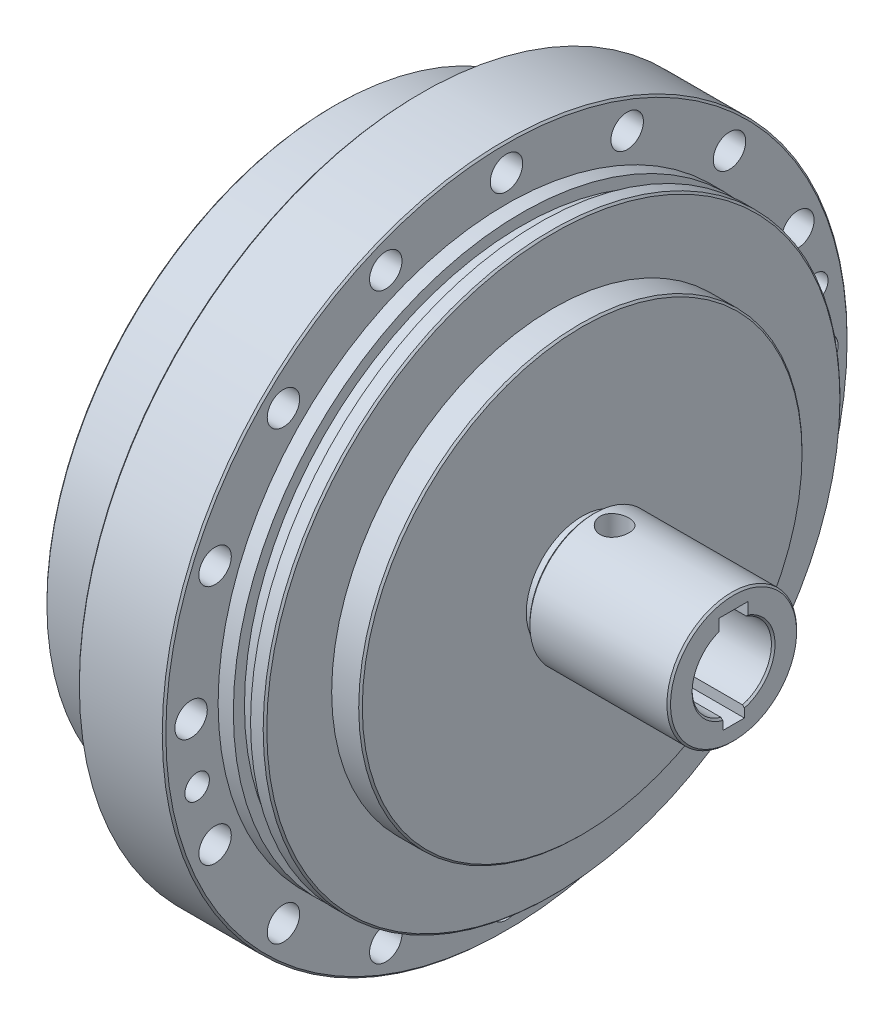
SolidWorks part; units mm, degrees
ref_plane "前视基准面" through (0, 0, 0) normal (0, 0, 1) x (1, 0, 0)
ref_plane "上视基准面" through (0, 0, 0) normal (0, 1, 0) x (1, 0, 0)
ref_plane "右视基准面" through (0, 0, 0) normal (1, 0, 0) x (0, 0, -1)
sketch "草图1" plane through (0, 0, 0) normal (0, 0, 1) x (1, 0, 0)
  line L0 (0, 0) -> (186.6546, 0) construction
  line L1 (3.8, 15.5) -> (3.8, 25)
  line L2 (3.8, 25) -> (0, 25)
  line L3 (0, 25) -> (0, 67.5)
  line L4 (0, 67.5) -> (7, 67.5)
  line L5 (7, 67.5) -> (7, 80)
  line L6 (7, 80) -> (31, 80)
  line L7 (31, 80) -> (31, 95)
  line L8 (31, 95) -> (55, 95)
  line L9 (55, 95) -> (55, 80)
  line L10 (55, 80) -> (59.22, 80)
  line L11 (59.22, 80) -> (59.22, 76.915)
  line L12 (59.22, 76.915) -> (64, 76.915)
  line L13 (64, 76.915) -> (64, 80)
  line L14 (64, 80) -> (68, 80)
  line L15 (68, 80) -> (68, 61.5)
  line L16 (76, 15.5) -> (3.8, 15.5)
  line L17 (56, 14.75) -> (56, 13.25)
  line L18 (68, 61.5) -> (76, 61.5)
  line L19 (76, 61.5) -> (76, 15.5)
  line L21 (3, 12) -> (3, 0)
  line L22 (79, 18) -> (118, 18)
  line L23 (118, 18) -> (118, 0)
  line L24 (79, 18) -> (79, 14.75)
  line L25 (79, 14.75) -> (56, 14.75)
  line L26 (3, 0) -> (118, 0)
  line L27 (56, 13.25) -> (33.25, 13.25)
  line L28 (33.25, 13.25) -> (32, 12)
  line L29 (32, 12) -> (3, 12)
  dimension "D1" = 3.8
  dimension "D3" = 67.5
  dimension "D4" = 7
  dimension "D5" = 31
  dimension "D6" = 80
  dimension "D7" = 95
  dimension "D8" = 24
  dimension "D9" = 80
  dimension "D10" = 68
  dimension "D11" = 4
  dimension "D12" = 4.78
  dimension "D13" = 76.915
  dimension "D14" = 61.5
  dimension "D15" = 76
  dimension "D16" = 31
  dimension "D17" = 53
  dimension "D18" = 29.5
  dimension "D19" = 24
  dimension "D20" = 3
  dimension "D21" = 25
  dimension "D22" = 18
  dimension "D23" = 115
  dimension "D24" = 76
  dimension "D25" = 26.5
  dimension "D26" = 135
  dimension "D27" = 29
revolve "旋转1" add sketch "草图1" angle 360 about L0
chamfer "倒角1" distance 0.5 angle 45 7 edges at (0, 0, 67.5) (68, 0, 80) (3.8, 0, 15.5) (55, 0, 95) (31, 0, 95) (7, 0, 80) (76, 0, 61.5)
sketch "草图2" plane through (55, 0, 0) normal (1, 0, 0) x (0, 0, -1)
  circle A0 centre (0, 87.5) radius 4.5
  circle A1 centre (0, 0) radius 87.5 construction
  dimension "D1" = 9
  dimension "D2" = 87.5
extrude "切除-拉伸1" cut sketch "草图2" against normal up to next
pattern_circular "阵列(圆周)1" count 16 over 360 about axis through (0, 0, 0) along (1, 0, 0) of "切除-拉伸1"
sketch "草图3" plane through (0, 0, 0) normal (-1, 0, 0) x (0, 0, 1)
  line L0 (0, 0) -> (28.1052, -40.1385) construction
  line L1 (0, 0) -> (0, -49) construction
  line L2 (0, 0) -> (-28.1052, -40.1385) construction
  line L3 (0, 0) -> (49, 0) construction
  line L4 (0, 0) -> (-28.1052, 40.1385) construction
  line L5 (0, 0) -> (28.1052, 40.1385) construction
  circle A0 centre (0, 0) radius 49 construction
  point P9 (0, 42.5)
  point P10 (0, -42.5)
  dimension "D1" = 98
  dimension "D2" = 35
  dimension "D3" = 85
sketch "草图5" plane through (31, 0, 0) normal (-1, 0, 0) x (0, 0, 1)
  line L0 (0, 0) -> (-85.8187, 17.0704) construction
  line L1 (0, 0) -> (-87.5, 0) construction
  line L2 (0, 0) -> (85.8187, -17.0704) construction
  dimension "D1" = 87.5
  dimension "D2" = 11.25
  dimension "D4" = 180
  dimension "D3" = 2
hole_wizard "M8 螺纹孔1" positions "3D草图2" profile "草图7" tap size "M8" standard "Gb" end condition through all
sketch3d "3D草图2"
  point P0 (31, 17.0704, -85.8187)
  point P3 (31, -17.0704, 85.8187)
sketch "草图7" plane through (31, 17.0704, -85.8187) normal (0, 1, 0) x (0, 0, 1)
  line L0 (0, 0) -> (0, 87)
  line L1 (0, 87) -> (3.4, 87)
  line L2 (3.4, 87) -> (3.4, 0)
  line L5 (3.4, 0) -> (0, 0)
  line L11 (0, -6.35) -> (0, 107.95) construction
  dimension "通孔螺纹孔钻头直径" = 6.8
  dimension "通孔螺纹孔钻头深度" = 87
cosmetic thread "孔螺蚊线7" parameters "D2"=8
cosmetic thread "孔螺蚊线8" parameters "D2"=8
hole_wizard "M14 螺纹孔1" positions "3D草图3" profile "草图8" tap size "M14" standard "Gb"
sketch3d "3D草图3"
  point P0 (0, -40.1385, -28.1052)
  point P6 (0, -40.1385, 28.1052)
  point P9 (0, 40.1385, 28.1052)
  point P15 (0, 40.1385, -28.1052)
  point P19 (0, -42.5, 0)
  point P22 (0, 42.5, 0)
sketch "草图8" plane through (0, -40.1385, -28.1052) normal (0, 1, 0) x (0, 0, 1)
  line L0 (0, 0) -> (0, 27.6052)
  line L1 (0, 27.6052) -> (6, 24)
  line L2 (6, 24) -> (6, 0)
  line L5 (6, 0) -> (0, 0)
  line L10 (0, 27.6052) -> (-6, 24) construction
  line L11 (0, -6.35) -> (0, 107.95) construction
  dimension "螺纹孔钻头直径" = 12
  dimension "螺纹孔钻头深度" = 24
  dimension "导头角度" = 118
cosmetic thread "孔螺蚊线9" parameters "D1"=18, "D2"=14
cosmetic thread "孔螺蚊线11" parameters "D1"=18, "D2"=14
cosmetic thread "孔螺蚊线12" parameters "D1"=18, "D2"=14
cosmetic thread "孔螺蚊线14" parameters "D1"=18, "D2"=14
cosmetic thread "孔螺蚊线15" parameters "D1"=18, "D2"=14
cosmetic thread "孔螺蚊线16" parameters "D1"=18, "D2"=14
sketch "草图11" plane through (118, 0, 0) normal (1, 0, 0) x (0, 0, -1)
  line L0 (-3.9, 14) -> (3.9, 14)
  line L1 (-4, 13.9) -> (-4, 10.247)
  line L2 (4, 10.247) -> (4, 13.9)
  line L3 (0, 0) -> (0, 28.1049) construction
  arc A0 (-4, 10.247) -> (4, 10.247) centre (0, 0) ccw
  arc A1 (-3.9, 14) -> (-4, 13.9) centre (-3.9, 13.9) ccw
  arc A2 (4, 13.9) -> (3.9, 14) centre (3.9, 13.9) ccw
  dimension "D1" = 11
  dimension "D4" = 0.1
  dimension "D2" = 8
  dimension "D3" = 25
extrude "切除-拉伸2" cut sketch "草图11" against normal blind 33
sketch "草图12" plane through (0, 0, 0) normal (0, 1, 0) x (1, 0, 0)
  line L1 (118, -18) -> (118, 18) construction
  circle A0 centre (85, 0) radius 4
  dimension "D1" = 8
  dimension "D2" = 33
extrude "切除-拉伸3" cut sketch "草图12" along normal through all
sketch "草图14" plane through (0, 0, 0) normal (-1, 0, 0) x (0, 0, 1)
  line L0 (0, 0) -> (0, 61.5884) construction
  line L1 (4, 0) -> (-4, 0) construction
  circle A0 centre (-40, 0) radius 25
  circle A1 centre (40, 0) radius 25
  dimension "D1" = 50
  dimension "D2" = 40
extrude "切除-拉伸4" cut sketch "草图14" against normal blind 3
sketch "草图18" plane through (0, 0, 0) normal (0, 0, 1) x (1, 0, 0)
  line L0 (0, 0) -> (122.0525, 0) construction
  line L1 (85, 6) -> (73, 6)
  line L2 (85, -11) -> (85, 10.247) construction
  line L3 (73, 6) -> (69.5359, 0)
  line L4 (69.5359, 0) -> (85, 0)
  line L5 (85, 6) -> (85, 0)
  dimension "D1" = 12
  dimension "D2" = 60
  dimension "D3" = 12
revolve "切除-旋转1" cut sketch "草图18" angle 360 about L0
chamfer "倒角2" distance 0.5 angle 45 3 edges at (118, -11, 0) (118, 0, 18) (79, 0, 18)
sketch "草图19" plane through (118, 0, 0) normal (1, 0, 0) x (0, 0, -1)
  line L0 (0, 0) -> (0, -20.311) construction
  line L1 (-3, -10.583) -> (3, -10.583)
  line L2 (-3, -10.583) -> (-3, -13.5)
  line L3 (-3, -13.5) -> (3, -13.5)
  line L4 (3, -10.583) -> (3, -13.5)
  arc A0 (-4, 10.247) -> (4, 10.247) centre (0, 0) ccw construction
  dimension "D1" = 2.5
  dimension "D2" = 6
extrude "切除-拉伸5" cut sketch "草图19" against normal up to surface (33 mm away) up to face at (85, -0.5702, 0)
hole_wizard "M6 螺纹孔1" positions "草图21" profile "草图20" tap size "M6" standard "GB"
sketch "草图21" plane through (0, -13.5, 0) normal (0, 1, 0) x (1, 0, 0)
  line L0 (118, -17.5) -> (118, 17.5) construction
  point P0 (92, 0)
  dimension "D1" = 26
sketch "草图20" plane through (92, -13.5, 0) normal (1, 0, 0) x (0, 0, 1)
  line L0 (0, 0) -> (0, 81.5)
  line L1 (0, 81.5) -> (2.5, 81.5)
  line L2 (2.5, 81.5) -> (2.5, 0)
  line L5 (2.5, 0) -> (0, 0)
  line L11 (0, -6.35) -> (0, 107.95) construction
  dimension "通孔螺纹孔钻头直径" = 5
  dimension "通孔螺纹孔钻头深度" = 81.5
cosmetic thread "孔螺蚊线17" parameters "D2"=6
